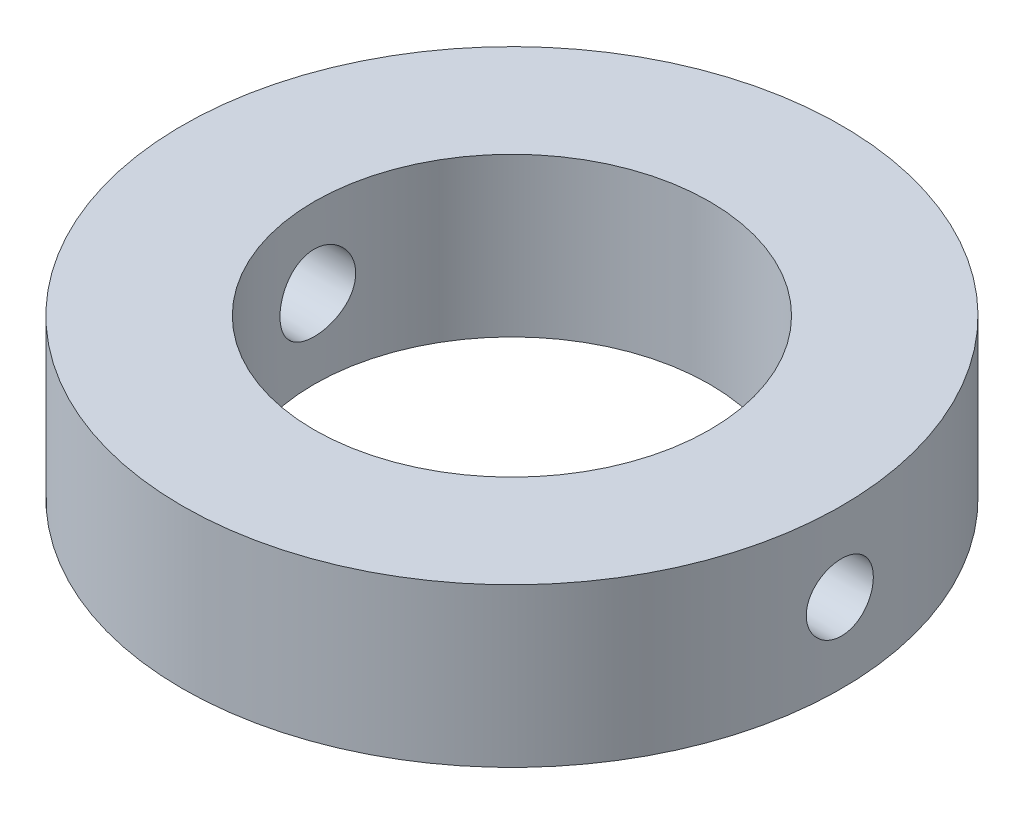
SolidWorks part; units mm, degrees
ref_plane "Front" through (0, 0, 0) normal (0, 0, 1) x (1, 0, 0)
ref_plane "Top" through (0, 0, 0) normal (0, 1, 0) x (1, 0, 0)
ref_plane "Right" through (0, 0, 0) normal (1, 0, 0) x (0, 0, -1)
sketch "Sketch1" plane through (0, 0, 0) normal (0, 1, 0) x (1, 0, 0)
  circle A0 centre (0, 0) radius 15
  circle A1 centre (0, 0) radius 25
  dimension "D1" = 50
  dimension "D2" = 30
extrude "Boss-Extrude1" add sketch "Sketch1" along normal blind 12
sketch "Sketch2" plane through (0, 0, 0) normal (0, 0, 1) x (1, 0, 0)
  line L0 (30, 6) -> (-30, 6)
  line L1 (-25, 0) -> (25, 0) construction
  line L2 (-30, 6) -> (-30, 9)
  line L3 (-30, 9) -> (30, 8.5)
  line L4 (30, 8.5) -> (30, 6)
  point P3 (0, 6)
  dimension "D1" = 60
  dimension "D2" = 6
  dimension "D3" = 3
  dimension "D4" = 2.5
revolve "Cut-Revolve1" cut sketch "Sketch2" angle 360 about L0
scale "Scale1" scale about centroid uniform scaling yes scale factor 0.33
